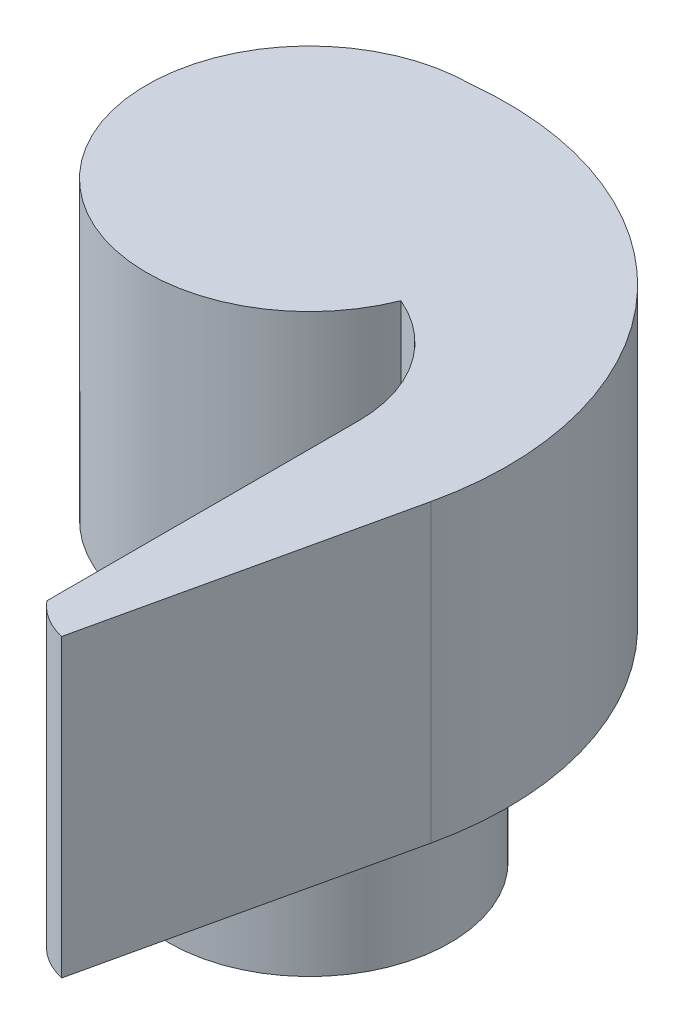
SolidWorks part; units mm, degrees
ref_plane "Front Plane" through (0, 0, 0) normal (0, 0, 1) x (1, 0, 0)
ref_plane "Top Plane" through (0, 0, 0) normal (0, 1, 0) x (1, 0, 0)
ref_plane "Right Plane" through (0, 0, 0) normal (1, 0, 0) x (0, 0, -1)
sketch "Sketch1" plane through (0, 0, 0) normal (0, 1, 0) x (1, 0, 0)
  line L0 (18.4245, -35.1774) -> (23.006, -14.8005)
  line L1 (15.8331, -33.5899) -> (15.8331, -12.488)
  arc A1 (0, 11) -> (10.2279, -4.0485) centre (0, 0) ccw
  arc A2 (23.006, -14.8005) -> (0, 11) centre (2.2654, -10.1373) ccw
  arc A3 (18.4245, -35.1774) -> (15.8331, -33.5899) centre (19.4579, -30.5814) cw
  arc A4 (15.8331, -12.488) -> (10.2279, -4.0485) centre (6.677, -12.488) ccw
  dimension "D1" = 22
  dimension "D2" = 21.2583
  dimension "D3" = 4.7107
  dimension "D4" = 9.156
  dimension "D5" = 2.2654
  dimension "D6" = 6.677
  dimension "D7" = 10.2279
  dimension "D8" = 18.4245
  dimension "D9" = 19.4579
extrude "Boss-Extrude1" add sketch "Sketch1" along normal blind 20
sketch "Sketch2" plane through (0, 0, 0) normal (0, -1, 0) x (1, 0, 0)
  circle A0 centre (0, 0) radius 9.5
  dimension "D1" = 19
extrude "Boss-Extrude2" add sketch "Sketch2" along normal blind 20
